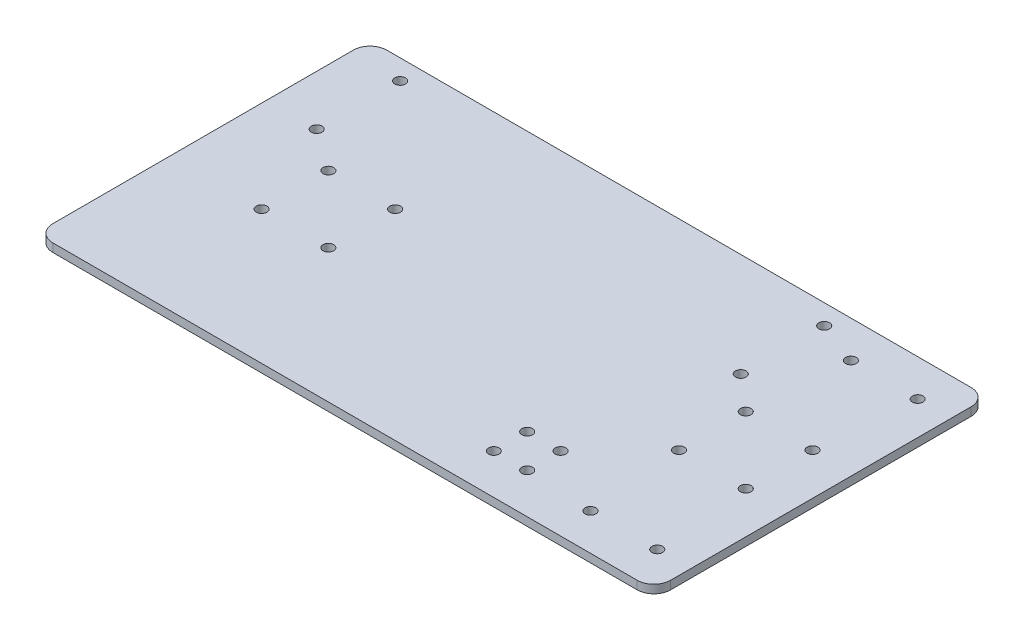
SolidWorks part; units mm, degrees
ref_plane "Front Plane" through (0, 0, 0) normal (0, 0, 1) x (1, 0, 0)
ref_plane "Top Plane" through (0, 0, 0) normal (0, 1, 0) x (1, 0, 0)
ref_plane "Right Plane" through (0, 0, 0) normal (1, 0, 0) x (0, 0, -1)
sketch "Sketch1" plane through (0, 0, 0) normal (0, 1, 0) x (1, 0, 0)
  line L0 (117.475, -35.4965) -> (53.975, -35.4965) construction
  line L1 (-117.475, 63.5) -> (117.475, 63.5)
  line L2 (-117.475, 63.5) -> (-117.475, -63.5)
  line L3 (-117.475, -63.5) -> (117.475, -63.5)
  line L4 (117.475, 63.5) -> (117.475, -63.5)
  line L5 (-117.475, 63.5) -> (117.475, -63.5) construction
  line L6 (-117.475, -63.5) -> (117.475, 63.5) construction
  line L7 (117.475, -49.53) -> (104.775, -49.53) construction
  line L8 (104.775, -49.53) -> (79.375, -49.53) construction
  line L9 (117.475, 49.53) -> (104.775, 49.53) construction
  line L10 (104.775, 49.53) -> (79.375, 49.53) construction
  line L11 (53.975, -35.4965) -> (41.275, -35.4965) construction
  line L12 (41.275, -35.4965) -> (41.275, -48.1965) construction
  line L13 (41.275, -48.1965) -> (53.975, -48.1965) construction
  line L14 (53.975, -48.1965) -> (53.975, -35.4965) construction
  line L15 (117.475, 55.88) -> (-98.425, 55.88) construction
  line L16 (-98.425, 55.88) -> (-98.425, 24.13) construction
  line L17 (62.865, 55.88) -> (62.865, 24.13) construction
  line L18 (-82.55, 0) -> (0, 0) construction
  line L19 (-82.55, -12.7) -> (-82.55, 12.7) construction
  line L20 (-57.15, -12.7) -> (-57.15, 12.7) construction
  line L21 (0, 0) -> (101.6, 0) construction
  line L22 (101.6, 12.7) -> (101.6, -12.7) construction
  line L23 (76.2, -12.7) -> (76.2, 12.7) construction
  circle A0 centre (79.375, 49.53) radius 2.032
  circle A1 centre (79.375, -49.53) radius 2.032
  circle A2 centre (104.775, -49.53) radius 2.032
  circle A3 centre (104.775, 49.53) radius 2.032
  circle A4 centre (53.975, -35.4965) radius 2.032
  circle A5 centre (41.275, -35.4965) radius 2.032
  circle A6 centre (41.275, -48.1965) radius 2.032
  circle A7 centre (53.975, -48.1965) radius 2.032
  circle A8 centre (-98.425, 55.88) radius 2.032
  circle A9 centre (-98.425, 24.13) radius 2.032
  circle A10 centre (62.865, 55.88) radius 2.032
  circle A11 centre (62.865, 24.13) radius 2.032
  circle A12 centre (-82.55, 12.7) radius 2.032
  circle A13 centre (-57.15, 12.7) radius 2.032
  circle A14 centre (-82.55, -12.7) radius 2.032
  circle A15 centre (-57.15, -12.7) radius 2.032
  circle A16 centre (76.2, -12.7) radius 2.032
  circle A17 centre (101.6, -12.7) radius 2.032
  circle A18 centre (76.2, 12.7) radius 2.032
  circle A19 centre (101.6, 12.7) radius 2.032
  point P0 (0, 0)
  point P36 (89.5068, 13.1564)
  point P37 (0, 0)
  point P40 (-82.55, 0)
  point P43 (-57.15, 0)
  point P48 (70.4103, -13.1564)
  point P58 (101.6, 0)
  point P61 (76.2, 0)
  dimension "D7" = 4.064
  dimension "D16" = 4.064
  dimension "D17" = 4.064
  dimension "D1" = 234.95
  dimension "D2" = 127
  dimension "D3" = 12.7
  dimension "D4" = 25.4
  dimension "D5" = 13.97
  dimension "D6" = 13.97
  dimension "D8" = 63.5
  dimension "D9" = 12.7
  dimension "D10" = 28.0035
  dimension "D11" = 12.7
  dimension "D12" = 31.75
  dimension "D13" = 215.9
  dimension "D14" = 54.61
  dimension "D15" = 7.62
  dimension "D18" = 25.4
  dimension "D19" = 25.4
  dimension "D20" = 82.55
  dimension "D21" = 25.4
  dimension "D22" = 25.4
  dimension "D23" = 101.6
extrude "Boss-Extrude1" add sketch "Sketch1" along normal blind 3.175
fillet "Fillet1" radius 6.35 4 edges at (-117.475, 1.5875, -63.5) (-117.475, 1.5875, 63.5) (117.475, 1.5875, -63.5) (117.475, 1.5875, 63.5)
